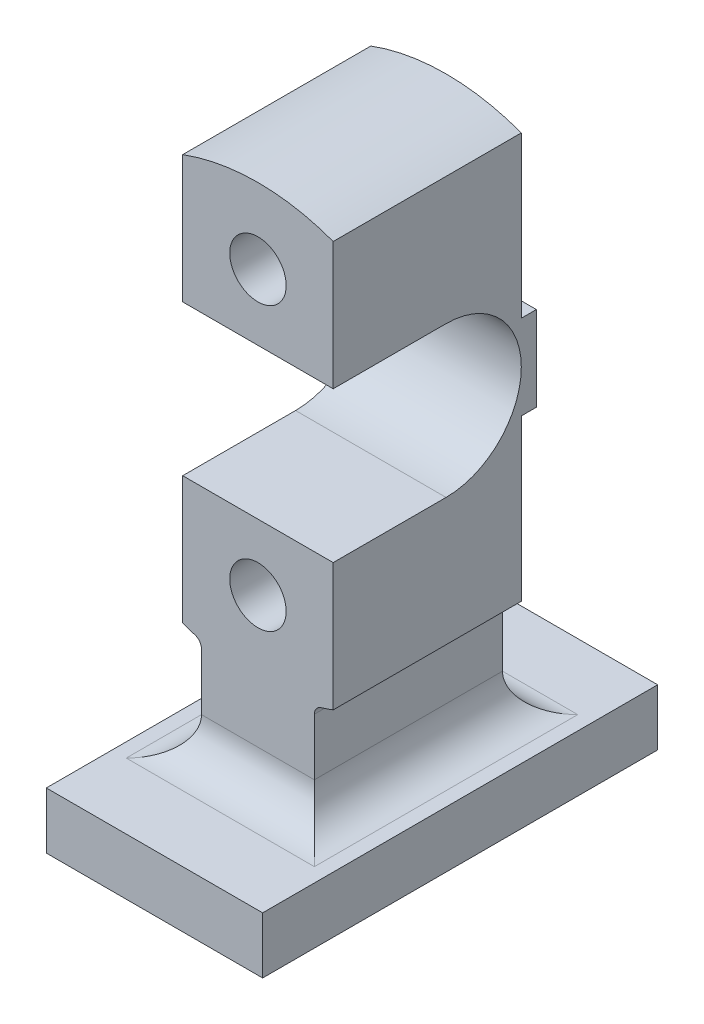
SolidWorks part; units mm, degrees
ref_plane "Front Plane" through (0, 0, 0) normal (0, 0, 1) x (1, 0, 0)
ref_plane "Top Plane" through (0, 0, 0) normal (0, 1, 0) x (1, 0, 0)
ref_plane "Right Plane" through (0, 0, 0) normal (1, 0, 0) x (0, 0, -1)
sketch "Sketch2" plane through (0, 0, 0) normal (0, 0, 1) x (1, 0, 0)
  line L0 (-30, 65.2176) -> (-30, 15)
  line L1 (-57.5, -15) -> (57.5, -15)
  line L2 (-57.5, -15) -> (-57.5, 15)
  line L3 (-57.5, 15) -> (-30, 15)
  line L4 (57.5, -15) -> (57.5, 15)
  line L5 (-57.5, -15) -> (57.5, 15) construction
  line L6 (-57.5, 15) -> (57.5, -15) construction
  line L7 (0, 0) -> (0, 285.7735) construction
  line L8 (30, 65.2176) -> (30, 15)
  line L9 (40, 287.8193) -> (40, 72.1807)
  line L10 (-40, 287.8193) -> (-40, 72.1807)
  line L12 (30, 15) -> (57.5, 15)
  arc A2 (-40, 72.1807) -> (-33.5417, 70.0002) centre (0, 180) ccw
  arc A3 (33.5417, 70.0002) -> (40, 72.1807) centre (0, 180) ccw
  arc A4 (30, 65.2176) -> (33.5417, 70.0002) centre (35, 65.2176) cw
  arc A5 (-33.5417, 70.0002) -> (-30, 65.2176) centre (-35, 65.2176) cw
  circle A6 centre (0, 105) radius 15
  circle A7 centre (0, 255) radius 15
  arc A8 (-40, 287.8193) -> (40, 287.8193) centre (0, 180) cw
  point P0 (0, 0)
  point P12 (-40, 15)
  point P14 (-30, 15)
  point P21 (30, 68.982)
  dimension "D5" = 115
  dimension "D7" = 5
  dimension "D10" = 30
  dimension "D12" = 115
  dimension "D1" = 115
  dimension "D2" = 30
  dimension "D4" = 60
  dimension "D6" = 165
  dimension "D8" = 80
  dimension "D9" = 90
  dimension "D11" = 150
extrude "Boss-Extrude2" add sketch "Sketch2" against normal blind 210 contours L1 L4 L3 L2
ref_plane "Plane1" through (0, 0, -105) normal (0, 0, 1) x (1, 0, 0)
sketch "Sketch7" plane through (40, 0, 0) normal (1, 0, 0) x (0, 0, -1)
  line L0 (155, 304.9244) -> (155, 15)
  line L1 (105, 295) -> (105, 72.1807) construction
  line L2 (210, 295) -> (0, 295) construction
  line L3 (210, 72.1807) -> (0, 72.1807) construction
  line L4 (55, 304.9244) -> (55, 15)
  line L5 (55, 304.9244) -> (155, 304.9244)
  line L6 (55, 15) -> (155, 15)
  line L7 (210, 15) -> (0, 15) construction
  dimension "D1" = 100
extrude "Cut-Extrude3" cut sketch "Sketch7" against normal through all flip side to cut
sketch "Sketch8" plane through (40, 0, 0) normal (-1, 0, 0) x (0, 0, 1)
  line L0 (-210, 15) -> (0, 15)
  line L1 (0, 15) -> (0, -15)
  line L2 (0, -15) -> (-210, -15)
  line L3 (-210, -15) -> (-210, 15)
extrude "Boss-Extrude6" add sketch "Sketch8" along normal blind 115 from surface at -17.5 starting at face at (57.5, 0, -105)
fillet "Fillet2" radius 20 4 edges at (0, 15, -155) (30, 15, -105) (0, 15, -55) (-30, 15, -105)
sketch "Sketch9" plane through (40, 0, 0) normal (1, 0, 0) x (0, 0, -1)
  line L0 (155, 202.5) -> (163, 202.5)
  line L1 (155, 72.1807) -> (155, 287.8193) construction
  line L2 (163, 202.5) -> (163, 157.5)
  line L3 (163, 157.5) -> (155, 157.5)
  line L4 (155, 157.5) -> (155, 202.5)
  line L5 (210, 15) -> (0, 15) construction
  point P6 (155, 180)
  point P7 (163, 158.6482)
  dimension "D1" = 22.5
  dimension "D2" = 8
  dimension "D3" = 165
extrude "Boss-Extrude7" add sketch "Sketch9" against normal up to surface (80 mm away) up to face at (-40, 180, -105)
sketch "Sketch10" plane through (40, 0, 0) normal (1, 0, 0) x (0, 0, -1)
  line L0 (163, 180) -> (55, 180) construction
  line L1 (163, 157.5) -> (163, 202.5) construction
  line L2 (55, 287.8193) -> (55, 72.1807) construction
  line L3 (115, 301.596) -> (115, 35) construction
  line L4 (55, 35) -> (155, 35) construction
  line L5 (155, 202.5) -> (155, 287.8193) construction
  line L6 (115, 220) -> (55, 220)
  line L7 (55, 220) -> (55, 140)
  line L8 (55, 140) -> (115, 140)
  arc A0 (115, 220) -> (115, 140) centre (115, 180) cw
  dimension "D2" = 40
  dimension "D1" = 40
extrude "Cut-Extrude4" cut sketch "Sketch10" against normal through all contours L8 A0 L6 L7
